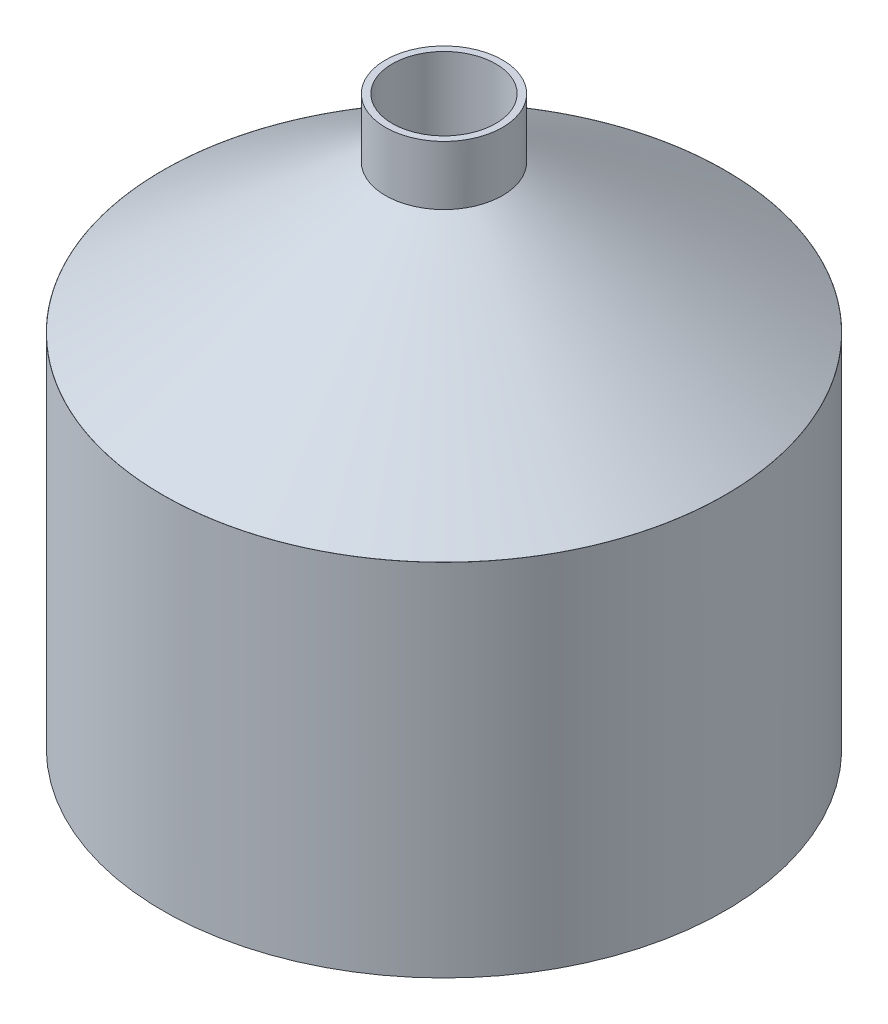
SolidWorks part; units mm, degrees
ref_plane "Front Plane" through (0, 0, 0) normal (0, 0, 1) x (1, 0, 0)
ref_plane "Top Plane" through (0, 0, 0) normal (0, 1, 0) x (1, 0, 0)
ref_plane "Right Plane" through (0, 0, 0) normal (1, 0, 0) x (0, 0, -1)
sketch "Sketch1" plane through (0, 0, 0) normal (0, 1, 0) x (1, 0, 0)
  circle A0 centre (0, 0) radius 62.5
  circle A1 centre (0, 0) radius 61.5
extrude "Boss-Extrude1" add sketch "Sketch1" along normal blind 80
sketch "Sketch2" plane through (0, 0, 0) normal (0, 0, 1) x (1, 0, 0)
  line L0 (0, 80) -> (-61.5, 80) construction
  line L1 (62.5, 80) -> (-62.5, 80) construction
  line L2 (-62.4726, 80) -> (-62.4726, 79.2769)
  line L3 (-62.4726, 79.2769) -> (-61.5, 79.2769)
  line L4 (-61.5, 79.2769) -> (-61.5, 80)
  line L5 (0, 80) -> (0, 130) construction
  line L6 (-8, 129.9955) -> (-4.8, 129.9955)
  line L7 (-8, 129.9955) -> (-8, 127)
  line L8 (-6.8, 127) -> (-6.8, 117)
  line L9 (-8, 127) -> (-6.8, 127)
  line L10 (-6.8, 117) -> (-62.4726, 80)
  line L11 (-61.5, 80) -> (-4.8, 117.6828)
  line L12 (-4.8, 117.6828) -> (-4.8, 129.9955)
  dimension "D1" = 0.5383
revolve "Revolve1" add sketch "Sketch2" angle 360 about L5
sketch "Sketch3" plane through (0, 0, 0) normal (0, 0, 1) x (1, 0, 0)
  line L0 (0, 0) -> (0, 9.876) construction
  line L2 (-3.8, 21.7062) -> (3.8, 21.7062)
  line L3 (-3.8, 21.7062) -> (-3.8, -1.9542)
  line L4 (-3.8, -1.9542) -> (3.8, -1.9542)
  line L5 (3.8, 21.7062) -> (3.8, -1.9542)
  line L6 (-3.8, 21.7062) -> (3.8, -1.9542) construction
  line L7 (-3.8, -1.9542) -> (3.8, 21.7062) construction
extrude "Cut-Extrude1" cut sketch "Sketch3" against normal blind 80
sketch "Sketch4" plane through (0, 0, 0) normal (0, 1, 0) x (1, 0, 0)
  circle A0 centre (0, 0) radius 71.44
sketch "Sketch5" plane through (0, 0, 0) normal (0, 1, 0) x (1, 0, 0)
  circle A0 centre (0, 0) radius 12.3
extrude "Cut-Extrude3" cut sketch "Sketch5" along normal blind 229
sketch "Sketch6" plane through (0, 0, 0) normal (0, 1, 0) x (1, 0, 0)
  circle A0 centre (0, 0) radius 11.5
  circle A1 centre (0, 0) radius 13
extrude "Boss-Extrude3" add sketch "Sketch6" along normal blind 20 from offset 106
